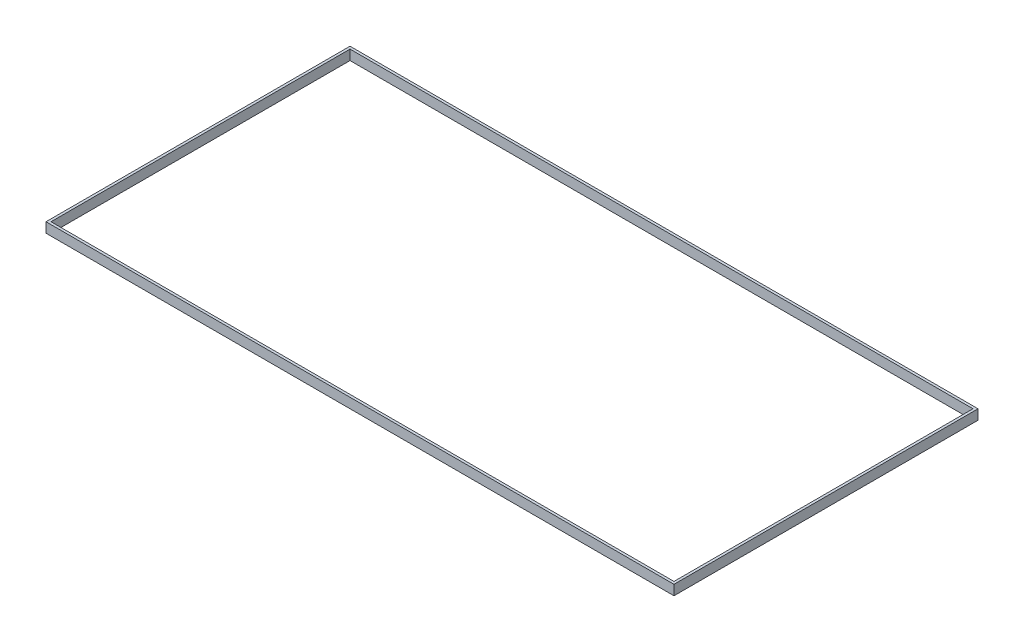
SolidWorks part; units mm, degrees
ref_plane "Front Plane" through (0, 0, 0) normal (0, 0, 1) x (1, 0, 0)
ref_plane "Top Plane" through (0, 0, 0) normal (0, 1, 0) x (1, 0, 0)
ref_plane "Right Plane" through (0, 0, 0) normal (1, 0, 0) x (0, 0, -1)
sketch "Sketch1" plane through (0, 0, 0) normal (0, 1, 0) x (1, 0, 0)
  line L1 (630, -305) -> (-630, -305)
  line L2 (630, -305) -> (630, 305)
  line L3 (630, 305) -> (-630, 305)
  line L4 (-630, -305) -> (-630, 305)
  line L5 (630, -305) -> (-630, 305) construction
  line L6 (630, 305) -> (-630, -305) construction
  line L7 (625, -300) -> (-625, -300)
  line L8 (625, -300) -> (625, 300)
  line L9 (625, 300) -> (-625, 300)
  line L10 (-625, -300) -> (-625, 300)
  line L11 (625, -300) -> (-625, 300) construction
  line L12 (625, 300) -> (-625, -300) construction
  point P0 (0, 0)
  point P6 (0, 0)
  dimension "D1" = 610
  dimension "D2" = 1260
  dimension "D3" = 600
  dimension "D4" = 1250
extrude "Boss-Extrude1" add sketch "Sketch1" along normal blind 20
